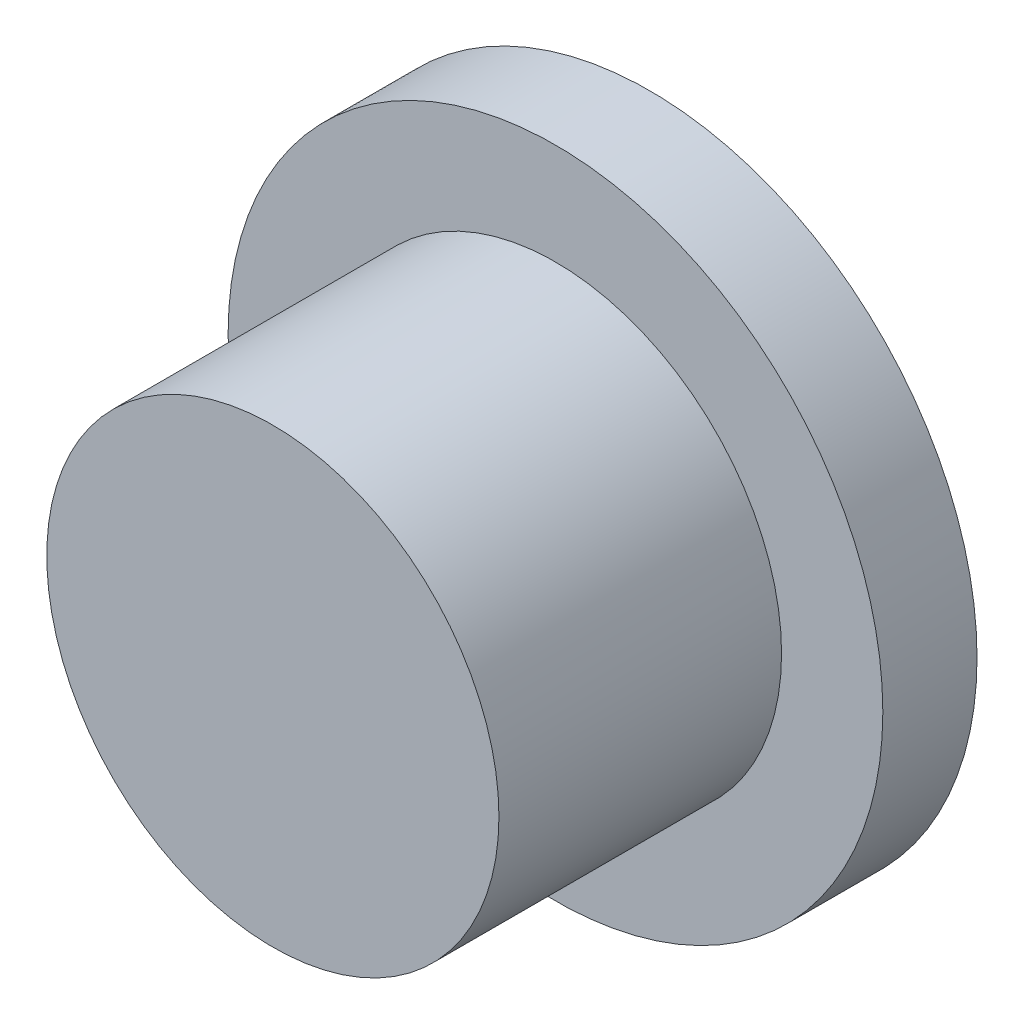
SolidWorks part; units mm, degrees
ref_plane "Ön Düzlem" through (0, 0, 0) normal (0, 0, 1) x (1, 0, 0)
ref_plane "Üst Düzlem" through (0, 0, 0) normal (0, 1, 0) x (1, 0, 0)
ref_plane "Sağ Düzlem" through (0, 0, 0) normal (1, 0, 0) x (0, 0, -1)
sketch "Çizim1" plane through (0, 0, 0) normal (0, 0, 1) x (1, 0, 0)
  circle A0 centre (0, 0) radius 6.95
  dimension "D1" = 13.9
extrude "Yükseklik-Ekstrüzyon1" add sketch "Çizim1" along normal blind 2
sketch "Çizim2" plane through (0, 0, 2) normal (0, 0, 1) x (1, 0, 0)
  circle A0 centre (0, 0) radius 4.8
  circle A1 centre (0, 0) radius 6.95
  circle A2 centre (0, 0) radius 6.95
  circle A3 centre (0, 0) radius 4.8
  dimension "D2" = 9.6
  dimension "D1" = 0
extrude "Yükseklik-Ekstrüzyon2" add sketch "Çizim2" along normal blind 6 contours A0
